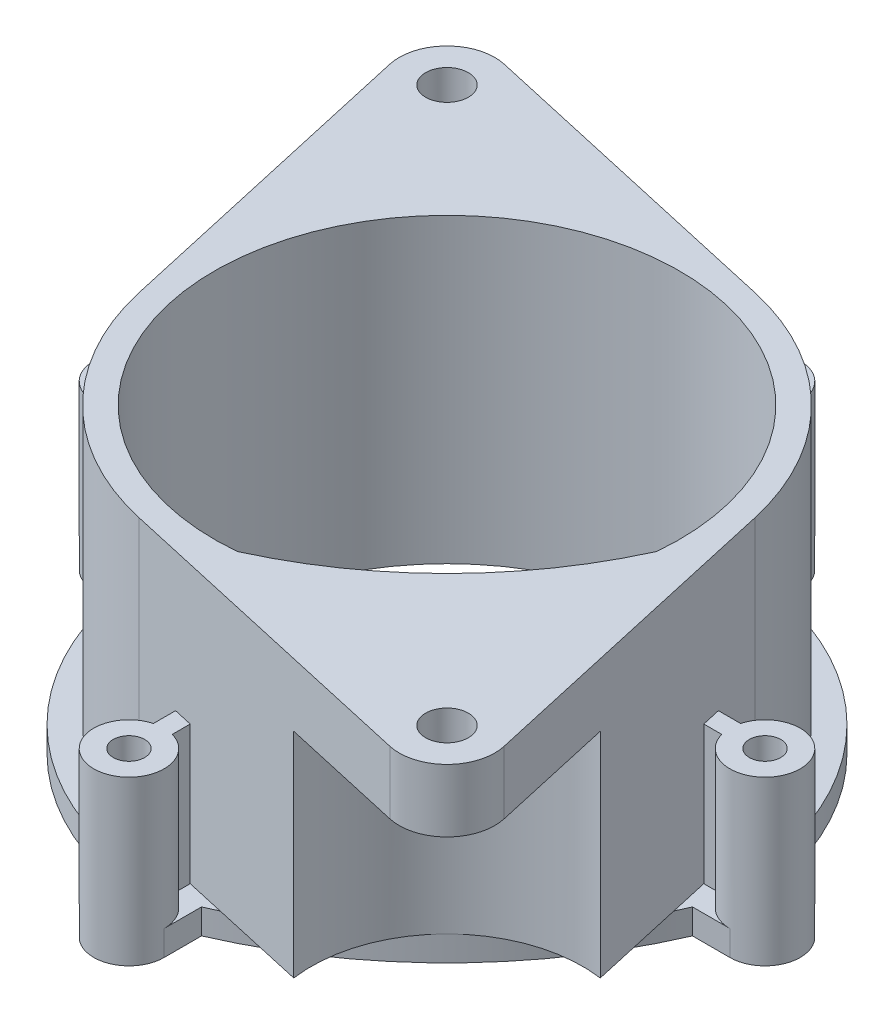
SolidWorks part; units mm, degrees
ref_plane "Спереди" through (0, 0, 0) normal (0, 0, 1) x (1, 0, 0)
ref_plane "Сверху" through (0, 0, 0) normal (0, 1, 0) x (1, 0, 0)
ref_plane "Справа" through (0, 0, 0) normal (1, 0, 0) x (0, 0, -1)
sketch "Эскиз1" plane through (0, 0, 0) normal (0, 1, 0) x (1, 0, 0)
  line L0 (22.3251, -2.8) -> (25.3, -2.8)
  line L1 (25.3, 2.8) -> (22.3251, 2.8)
  line L2 (2.8, 22.3251) -> (2.8, 25.3)
  line L3 (-2.8, 25.3) -> (-2.8, 22.3251)
  line L4 (-22.3251, 2.8) -> (-25.3, 2.8)
  line L5 (-25.3, -2.8) -> (-22.3251, -2.8)
  line L6 (-2.8, -22.3251) -> (-2.8, -25.3)
  line L7 (2.8, -25.3) -> (2.8, -22.3251)
  arc A0 (2.8, -22.3251) -> (22.3251, -2.8) centre (-12.1018, 12.1018) ccw
  arc A1 (25.3, -2.8) -> (25.3, 2.8) centre (25.3, 0) ccw
  arc A2 (22.3251, 2.8) -> (2.8, 22.3251) centre (0, 0) ccw
  arc A3 (2.8, 25.3) -> (-2.8, 25.3) centre (0, 25.3) ccw
  arc A4 (-2.8, 22.3251) -> (-22.3251, 2.8) centre (0, 0) ccw
  arc A5 (-25.3, 2.8) -> (-25.3, -2.8) centre (-25.3, 0) ccw
  arc A6 (-22.3251, -2.8) -> (-2.8, -22.3251) centre (0, 0) ccw
  arc A7 (-2.8, -25.3) -> (2.8, -25.3) centre (0, -25.3) ccw
  arc A10 (18.4175, -1.7451) -> (1.7451, -18.4175) centre (0, 0) ccw
  arc A11 (1.7451, -18.4175) -> (18.4175, -1.7451) centre (-12.1018, 12.1018) ccw
extrude "Бобышка-Вытянуть1" add sketch "Эскиз1" along normal blind 2
sketch "Эскиз2" plane through (0, 2, 0) normal (0, 1, 0) x (1, 0, 0)
  line L0 (-22.2291, -22.2291) -> (22.0426, 22.0426) construction
  line L1 (20.0033, 4.4854) -> (23.5575, -11.3649)
  line L2 (-4.4854, -20.0033) -> (11.3649, -23.5575)
  line L5 (-20.0033, -4.4854) -> (-24.0573, 13.5937)
  line L6 (4.4854, 20.0033) -> (-13.5937, 24.0573)
  arc A5 (20.0033, 4.4854) -> (4.4854, 20.0033) centre (0, 0) ccw
  arc A9 (-20.0033, -4.4854) -> (-4.4854, -20.0033) centre (0, 0) ccw
  arc A10 (1.7451, -18.4175) -> (18.4175, -1.7451) centre (-12.1018, 12.1018) ccw construction
  arc A11 (18.4175, -1.7451) -> (1.7451, -18.4175) centre (0, 0) ccw construction
  arc A12 (1.7451, -18.4175) -> (18.4175, -1.7451) centre (-12.1018, 12.1018) ccw
  arc A13 (18.4175, -1.7451) -> (1.7451, -18.4175) centre (0, 0) ccw
  arc A14 (-24.0573, 13.5937) -> (-13.5937, 24.0573) centre (-22.0617, 22.0617) ccw
  arc A15 (23.5575, -11.3649) -> (11.3649, -23.5575) centre (22.0617, -22.0617) ccw
extrude "Бобышка-Вытянуть2" add sketch "Эскиз2" along normal blind 17
sketch "Эскиз3" plane through (0, 19, 0) normal (0, 1, 0) x (1, 0, 0)
  line L0 (-22.2291, -22.2291) -> (22.0426, 22.0426) construction
  line L1 (20.0033, 4.4854) -> (25.7697, -21.2303)
  line L2 (-4.4854, -20.0033) -> (21.2303, -25.7697)
  line L3 (-20.0033, -4.4854) -> (-25.7697, 21.2303)
  line L4 (4.4854, 20.0033) -> (-21.2303, 25.7697)
  arc A0 (20.0033, 4.4854) -> (4.4854, 20.0033) centre (0, 0) ccw
  arc A1 (-21.2303, 25.7697) -> (-25.7697, 21.2303) centre (-22.0617, 22.0617) ccw
  arc A2 (25.7697, -21.2303) -> (21.2303, -25.7697) centre (22.0617, -22.0617) cw
  arc A3 (-20.0033, -4.4854) -> (-4.4854, -20.0033) centre (0, 0) ccw
extrude "Бобышка-Вытянуть3" add sketch "Эскиз3" along normal blind 5
hole_wizard "Отверстие с зазором M31" positions "Эскиз4" profile "Эскиз5" hole size "M3" standard "ISO" end condition through all
sketch "Эскиз4" plane through (0, 0, 0) normal (0, -1, 0) x (-1, 0, 0)
  point P1 (-22.0617, -22.0617)
  point P4 (22.0617, 22.0617)
sketch "Эскиз5" plane through (22.0617, 0, 22.0617) normal (1, 0, 0) x (0, 0, -1)
  line L0 (0, 0) -> (0, 24)
  line L1 (0, 24) -> (1.7, 24)
  line L2 (1.7, 24) -> (1.7, 0)
  line L5 (1.7, 0) -> (0, 0)
  line L11 (0, -6.35) -> (0, 107.95) construction
  dimension "Диаметр сквозного отверстия" = 3.4
  dimension "Глубина сквозного отверстия" = 24
sketch "Эскиз6" plane through (0, 2, 0) normal (0, 1, 0) x (1, 0, 0)
  line L0 (4.4854, 20.0033) -> (-21.2303, 25.7697) construction
  line L1 (0.75, 20.8409) -> (-0.75, 21.1772)
  line L2 (-21.1772, 0.75) -> (-22.6023, 0.75)
  line L3 (-25.7697, 21.2303) -> (-20.0033, -4.4854) construction
  line L4 (-22.6023, -0.75) -> (-20.8409, -0.75)
  line L5 (-21.1772, 0.75) -> (-20.8409, -0.75)
  line L6 (25.7697, -21.2303) -> (20.0033, 4.4854) construction
  line L7 (21.1772, -0.75) -> (20.8409, 0.75)
  line L8 (-0.75, 21.1772) -> (-0.75, 22.6023)
  line L10 (0.75, 22.6023) -> (0.75, 20.8409)
  line L11 (-4.4854, -20.0033) -> (21.2303, -25.7697) construction
  line L12 (22.6023, 0.75) -> (20.8409, 0.75)
  line L13 (-0.75, -20.8409) -> (0.75, -21.1772)
  line L14 (21.1772, -0.75) -> (22.6023, -0.75)
  line L16 (0.75, -22.6023) -> (0.75, -21.1772)
  line L18 (-0.75, -20.8409) -> (-0.75, -22.6023)
  arc A0 (0.75, 22.6023) -> (-0.75, 22.6023) centre (0, 25.3) ccw
  arc A1 (22.6023, -0.75) -> (22.6023, 0.75) centre (25.3, 0) ccw
  arc A2 (-0.75, -22.6023) -> (0.75, -22.6023) centre (0, -25.3) ccw
  arc A3 (-22.6023, 0.75) -> (-22.6023, -0.75) centre (-25.3, 0) ccw
extrude "Бобышка-Вытянуть4" add sketch "Эскиз6" along normal blind 11
sketch "Эскиз7" plane through (0, 19, 0) normal (0, -1, 0) x (1, 0, 0)
  arc A2 (18.4175, 1.7451) -> (1.7451, 18.4175) centre (-12.1018, -12.1018) ccw
  arc A3 (1.7451, 18.4175) -> (18.4175, 1.7451) centre (0, 0) ccw
  arc A4 (18.4175, 1.7451) -> (1.7451, 18.4175) centre (-12.1018, -12.1018) ccw
  arc A5 (1.7451, 18.4175) -> (18.4175, 1.7451) centre (0, 0) ccw
  dimension "D1" = 0
extrude "Вырез-Вытянуть1" cut sketch "Эскиз7" against normal blind 11
hole_wizard "Отверстие обработанное метчиком M31" positions "Эскиз8" profile "Эскиз9" tap size "M3" standard "ISO" end condition through all
sketch "Эскиз8" plane through (0, 0, 0) normal (0, -1, 0) x (-1, 0, 0)
  point P0 (0, -25.3)
  point P3 (-25.3, 0)
  point P6 (0, 25.3)
  point P9 (25.3, 0)
sketch "Эскиз9" plane through (0, 0, 25.3) normal (1, 0, 0) x (0, 0, -1)
  line L0 (0, 0) -> (0, 24)
  line L1 (0, 24) -> (1.25, 24)
  line L2 (1.25, 24) -> (1.25, 0)
  line L5 (1.25, 0) -> (0, 0)
  line L11 (0, -6.35) -> (0, 107.95) construction
  dimension "Диаметр проходного сверла" = 2.5
  dimension "Глубина проходного сверла" = 24
cosmetic thread "Отверстие резьбы1" parameters "D2"=3
cosmetic thread "Отверстие резьбы2" parameters "D2"=3
cosmetic thread "Отверстие резьбы3" parameters "D2"=3
cosmetic thread "Отверстие резьбы4" parameters "D2"=3
